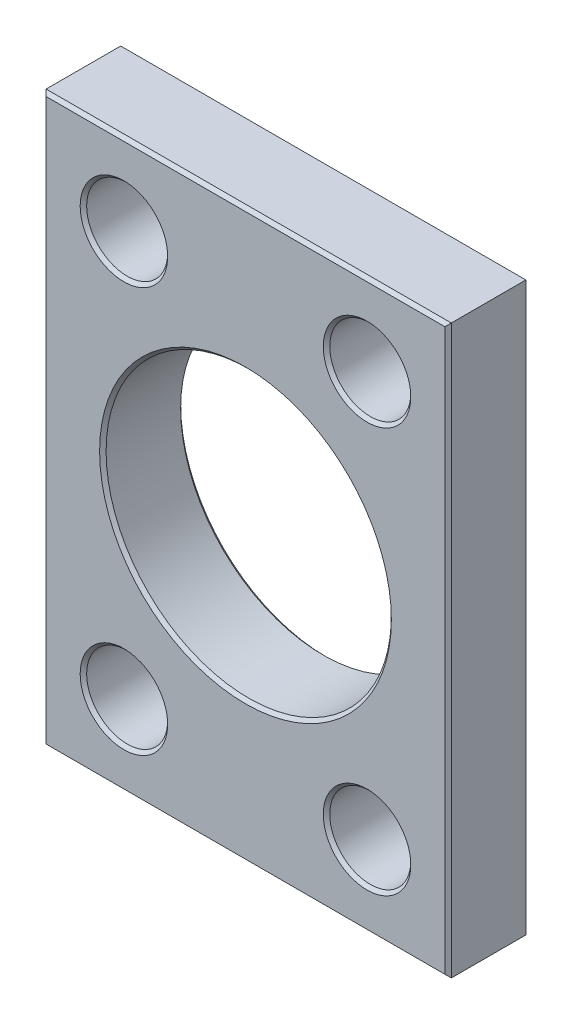
SolidWorks part; units mm, degrees
ref_plane "Front Plane" through (0, 0, 0) normal (0, 0, 1) x (1, 0, 0)
ref_plane "Top Plane" through (0, 0, 0) normal (0, 1, 0) x (1, 0, 0)
ref_plane "Right Plane" through (0, 0, 0) normal (1, 0, 0) x (0, 0, -1)
sketch "Sketch1" plane through (0, 0, 0) normal (0, 0, 1) x (1, 0, 0)
  line L0 (-9.525, 15.875) -> (-9.525, -15.875) construction
  line L1 (-15.875, -22.225) -> (15.875, -22.225)
  line L2 (-15.875, -22.225) -> (-15.875, 22.225)
  line L3 (-15.875, 22.225) -> (15.875, 22.225)
  line L4 (15.875, -22.225) -> (15.875, 22.225)
  line L5 (-15.875, -22.225) -> (15.875, 22.225) construction
  line L6 (-15.875, 22.225) -> (15.875, -22.225) construction
  line L7 (-9.525, -15.875) -> (9.525, -15.875) construction
  line L8 (9.525, -15.875) -> (9.525, 15.875) construction
  line L9 (9.525, 15.875) -> (-9.525, 15.875) construction
  line L10 (-9.525, 15.875) -> (9.525, -15.875) construction
  line L11 (9.525, 15.875) -> (-9.525, -15.875) construction
  circle A0 centre (-9.525, 15.875) radius 3.175
  circle A1 centre (9.525, 15.875) radius 3.175
  circle A2 centre (-9.525, -15.875) radius 3.175
  circle A3 centre (9.525, -15.875) radius 3.175
  circle A4 centre (0, 0) radius 11.176
  point P0 (0, 0)
  point P14 (0, 22.225)
  point P15 (0, 15.875)
  dimension "D5" = 6.35
  dimension "D7" = 22.352
  dimension "D1" = 19.05
  dimension "D2" = 31.75
  dimension "D3" = 44.45
  dimension "D4" = 6.35
  dimension "D6" = 31.75
extrude "Boss-Extrude1" add sketch "Sketch1" along normal blind 6.35
chamfer "Chamfer1" distance 0.254 angle 45 18 edges at (11.176, 0, 0) (-6.35, -15.875, 0) (-6.35, 15.875, 0) (0, 22.225, 0) (-15.875, 0, 0) (0, -22.225, 0) (15.875, 0, 0) (12.7, 15.875, 0) (12.7, -15.875, 0) (11.176, 0, 6.35) (12.7, -15.875, 6.35) (-6.35, -15.875, 6.35) (12.7, 15.875, 6.35) (-6.35, 15.875, 6.35) (0, -22.225, 6.35) (-15.875, 0, 6.35) (0, 22.225, 6.35) (15.875, 0, 6.35)
